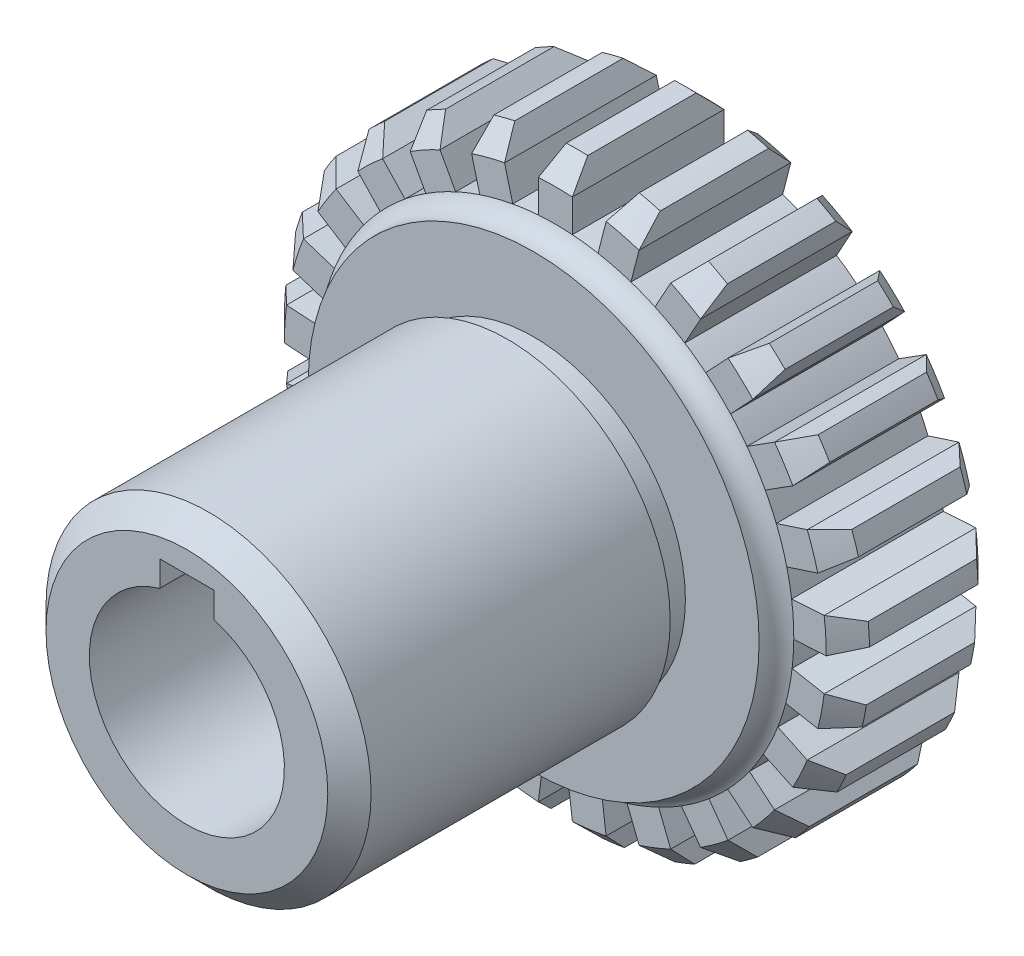
SolidWorks part; units mm, degrees
ref_plane "Спереди" through (0, 0, 0) normal (0, 0, 1) x (1, 0, 0)
ref_plane "Сверху" through (0, 0, 0) normal (0, 1, 0) x (1, 0, 0)
ref_plane "Справа" through (0, 0, 0) normal (1, 0, 0) x (0, 0, -1)
other "Configuration Table"
sketch "Эскиз1" plane through (0, 0, 0) normal (1, 0, 0) x (0, 0, -1)
  line L0 (-52.1029, 0) -> (-4.1029, 0) construction
  line L1 (-4.1029, 0) -> (-4.1029, 22)
  line L2 (-4.1029, 22) -> (-18.1029, 22)
  line L3 (-20.1029, 20.8) -> (-20.1029, 14)
  line L4 (-20.1029, 14) -> (-22.5029, 14)
  line L5 (-22.5029, 14) -> (-22.5029, 15)
  line L6 (-22.5029, 15) -> (-52.1029, 15)
  line L7 (-52.1029, 15) -> (-52.1029, 0)
  line L8 (-52.1029, 0) -> (-4.1029, 0)
  arc A0 (-20.1029, 20.8) -> (-18.1029, 22) centre (-19.9389, 22.7933) ccw
  dimension "D6" = 2
  dimension "D1" = 15
  dimension "D2" = 22
  dimension "D3" = 2.4
  dimension "D4" = 14
  dimension "D5" = 48
  dimension "D7" = 4.1029
  dimension "D8" = 14
  dimension "D9" = 19.9389
  dimension "D10" = 20.1029
revolve "Повернуть1" add sketch "Эскиз1" angle 360 about L0
chamfer "Фаска1" distance 2 angle 45 1 edges at (15, 0, 52.1029)
sketch "Эскиз2" plane through (0, 0, 4.1029) normal (0, 0, -1) x (-1, 0, 0)
  line L0 (-2.5, 11) -> (-2.5, 8.6458)
  line L1 (2.5, 11) -> (2.5, 8.6458)
  line L2 (-2.5, 11) -> (2.5, 11)
  arc A0 (-2.5, 8.6458) -> (2.5, 8.6458) centre (0, 0) ccw
  circle A1 centre (0, 0) radius 22 construction
  dimension "D1" = 9
  dimension "D2" = 2.5
  dimension "D3" = 11
extrude "Вырез-Вытянуть1" cut sketch "Эскиз2" against normal through all
sketch "Эскиз3" plane through (0, 0, 0) normal (1, 0, 0) x (0, 0, -1)
  line L0 (0, 0) -> (-36.3158, 0) construction
  line L1 (-4.1029, 9) -> (-4.1029, 12)
  line L2 (-4.1029, -22) -> (-4.1029, 22) construction
  line L5 (-8.1029, 9) -> (-4.1029, 12)
  line L6 (-8.1029, 9) -> (-4.1029, 9)
  dimension "D1" = 8.1029
  dimension "D2" = 9
  dimension "D3" = 12
revolve "Вырез-Повернуть1" cut sketch "Эскиз3" angle 360 about L0
sketch "Эскиз4" plane through (0, 0, 4.1029) normal (0, 0, -1) x (-1, 0, 0)
  line L2 (-1.5698, 24.9507) -> (-1.5698, 21.9439)
  line L3 (1.5698, 24.9507) -> (1.5698, 21.9439)
  line L4 (-1.5698, 24.9507) -> (-0.9943, 26.9817)
  line L5 (1.5698, 24.9507) -> (0.9943, 26.9817)
  circle A0 centre (0, 0) radius 25 construction
  arc A1 (0.9943, 26.9817) -> (-0.9943, 26.9817) centre (0, 0) ccw
  arc A2 (-1.5698, 24.9507) -> (1.5698, 24.9507) centre (0, 0) cw construction
  arc A6 (1.5698, 21.9439) -> (-1.5698, 21.9439) centre (0, 0) ccw
  circle A7 centre (0, 0) radius 12 construction
  dimension "D1" = 50
  dimension "D4" = 27
  dimension "D5" = 22
  dimension "D2" = 3.1416
  dimension "D3" = 1.9891
extrude "Бобышка-Вытянуть1" add sketch "Эскиз4" against normal blind 14
chamfer "Фаска2" distance 2 angle 45 2 edges at (0, 27, 18.1029) (0, 27, 4.1029)
pattern_circular "Круговой массив1" count 25 over 360 about axis through (0, 0, 0) along (0, 0, 1) of "Фаска2", "Бобышка-Вытянуть1"
